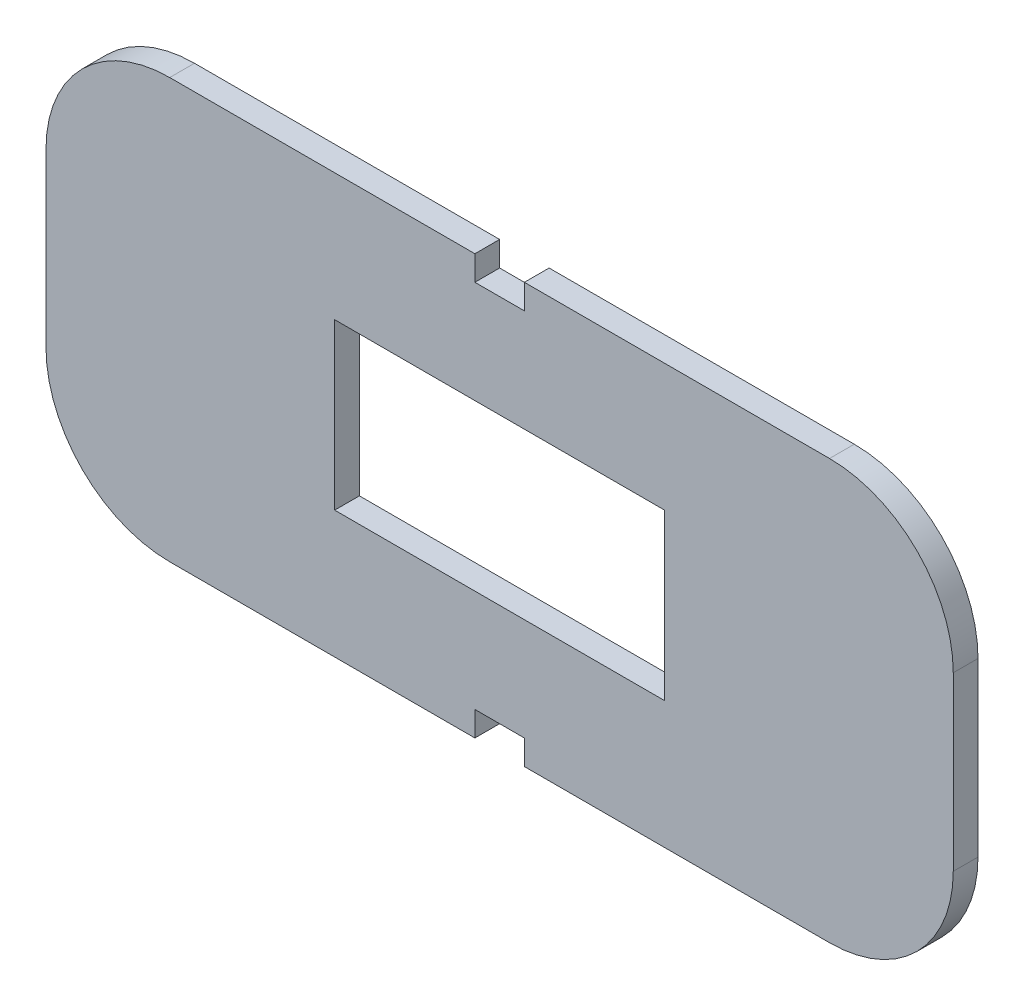
SolidWorks part; units mm, degrees
ref_plane "Front Plane" through (0, 0, 0) normal (0, 0, 1) x (1, 0, 0)
ref_plane "Top Plane" through (0, 0, 0) normal (0, 1, 0) x (1, 0, 0)
ref_plane "Right Plane" through (0, 0, 0) normal (1, 0, 0) x (0, 0, -1)
sketch "Sketch1" plane through (0, 0, 0) normal (0, 0, 1) x (1, 0, 0)
  line L0 (52, 50.85) -> (52, 47.85)
  line L1 (0, 0) -> (52, 0)
  line L2 (0, 0) -> (0, 50.85)
  line L3 (0, 50.85) -> (52, 50.85)
  line L4 (110, 0) -> (110, 50.85)
  line L5 (52, 47.85) -> (58, 47.85)
  line L6 (58, 47.85) -> (58, 50.85)
  line L7 (55, 47.85) -> (55, 50.85) construction
  line L8 (0, 25.425) -> (110, 25.425) construction
  line L10 (52, 0) -> (52, 3)
  line L11 (52, 3) -> (58, 3)
  line L12 (58, 3) -> (58, 0)
  line L14 (58, 50.85) -> (110, 50.85)
  line L15 (58, 0) -> (110, 0)
  line L17 (35, 15.425) -> (75, 15.425)
  line L18 (35, 15.425) -> (35, 35.425)
  line L19 (35, 35.425) -> (75, 35.425)
  line L20 (75, 15.425) -> (75, 35.425)
  line L21 (35, 15.425) -> (75, 35.425) construction
  line L22 (35, 35.425) -> (75, 15.425) construction
  point P17 (55, 25.425)
  dimension "D1" = 110
  dimension "D2" = 50.85
  dimension "D3" = 6
  dimension "D4" = 3
  dimension "D5" = 40
  dimension "D6" = 20
extrude "Boss-Extrude1" add sketch "Sketch1" along normal blind 3 contours L3 L0 L5 L6 L14 L4 L15 L12 L11 L10 L1 L2 | L18 L17 L20 L19
fillet "Fillet1" radius 15 4 edges at (0, 0, 1.5) (0, 50.85, 1.5) (110, 0, 1.5) (110, 50.85, 1.5)
